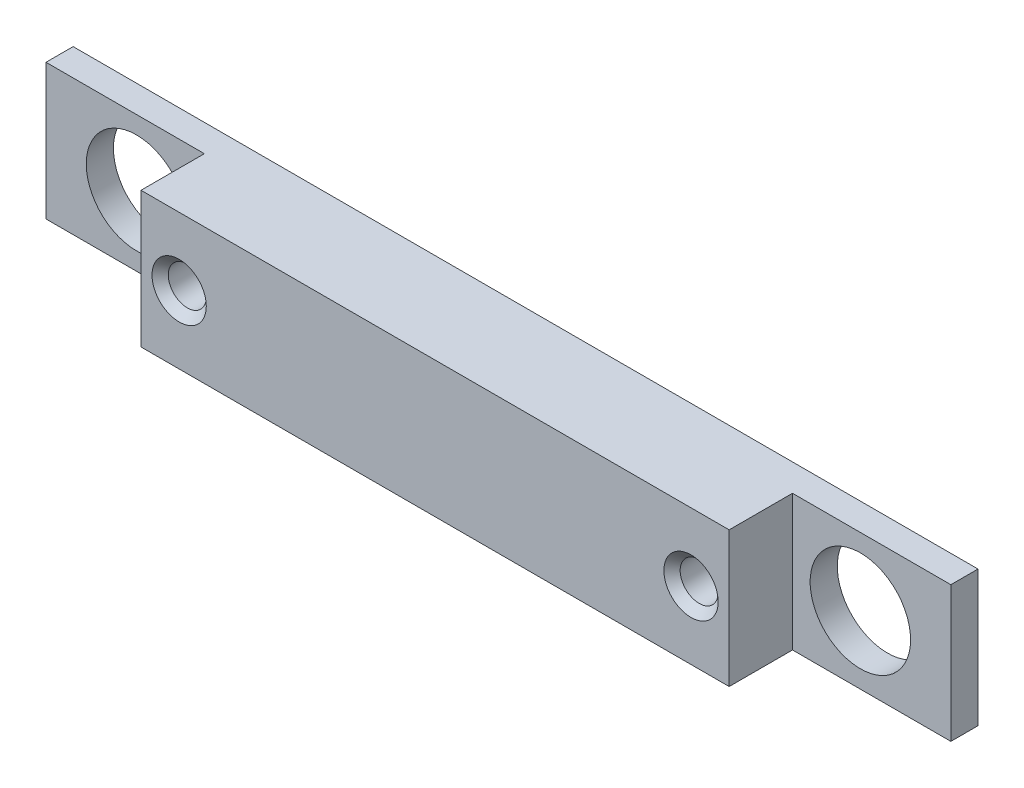
SolidWorks part; units mm, degrees
ref_plane "Front Plane" through (0, 0, 0) normal (0, 0, 1) x (1, 0, 0)
ref_plane "Top Plane" through (0, 0, 0) normal (0, 1, 0) x (1, 0, 0)
ref_plane "Right Plane" through (0, 0, 0) normal (1, 0, 0) x (0, 0, -1)
sketch "Sketch1" plane through (0, 0, 0) normal (0, 0, 1) x (1, 0, 0)
  line L1 (-50, -7.5) -> (50, -7.5)
  line L2 (-50, -7.5) -> (-50, 7.5)
  line L3 (-50, 7.5) -> (50, 7.5)
  line L4 (50, -7.5) -> (50, 7.5)
  line L5 (-50, -7.5) -> (50, 7.5) construction
  line L6 (-50, 7.5) -> (50, -7.5) construction
  point P0 (0, 0)
  dimension "D1" = 15
  dimension "D2" = 100
extrude "Boss-Extrude1" add sketch "Sketch1" along normal mid plane 10
hole_wizard "M5x0.8 Tapped Hole1" positions "Sketch4" profile "Sketch5" tap size "M5x0.8" standard "ANSI Metric"
sketch "Sketch4" plane through (0, 0, 5) normal (0, 0, 1) x (1, 0, 0)
  line L0 (-28.2845, 0) -> (28.2845, 0) construction
  line L2 (50, 7.5) -> (-50, 7.5) construction
  point P8 (-28.2845, 0)
  point P10 (28.2845, 0)
  dimension "D1" = 56.569
sketch "Sketch5" plane through (-28.2845, 0, 5) normal (1, 0, 0) x (0, -1, 0)
  line L0 (0, 0) -> (0, 13.6618)
  line L1 (0, 13.6618) -> (2.1, 12.4)
  line L2 (2.1, 12.4) -> (2.1, 0.9)
  line L3 (2.1, 0.9) -> (3, 0)
  line L5 (3, 0) -> (0, 0)
  line L6 (-2.1, 0.9) -> (-3, 0) construction
  line L10 (0, 13.6618) -> (-2.1, 12.4) construction
  line L11 (0, -6.35) -> (0, 107.95) construction
  dimension "Tap Drill Dia." = 4.2
  dimension "Tap Drill Depth" = 12.4
  dimension "Near C'Sink Dia." = 6
  dimension "Near C'Sink Angle" = 90
  dimension "Drill Angle" = 118
cosmetic thread "Hole Thread1" parameters "D1"=10, "D2"=5
cosmetic thread "Hole Thread2" parameters "D1"=10, "D2"=5
sketch "Sketch6" plane through (0, 0, -5) normal (0, 0, -1) x (-1, 0, 0)
  line L0 (0, 0) -> (40, 0) construction
  circle A0 centre (40, 0) radius 5.5499
  dimension "D2" = 11.0998
  dimension "D1" = 40
extrude "Cut-Extrude1" cut sketch "Sketch6" against normal through all
sketch "Sketch7" plane through (0, 0, -5) normal (0, 0, -1) x (-1, 0, 0)
  line L0 (50, -7.5) -> (-50, -7.5) construction
  line L1 (50, 7.5) -> (32.5, 7.5)
  line L2 (50, 7.5) -> (50, -7.5)
  line L3 (50, -7.5) -> (32.5, -7.5)
  line L4 (32.5, 7.5) -> (32.5, -7.5)
  circle A0 centre (40, 0) radius 5.5499 construction
  dimension "D1" = 7.5
extrude "Cut-Extrude2" cut sketch "Sketch7" against normal through all from offset 3 offset against normal yes
mirror "Mirror1" about plane through (0, 0, 0) normal (1, 0, 0) of "Cut-Extrude1", "Cut-Extrude2"
